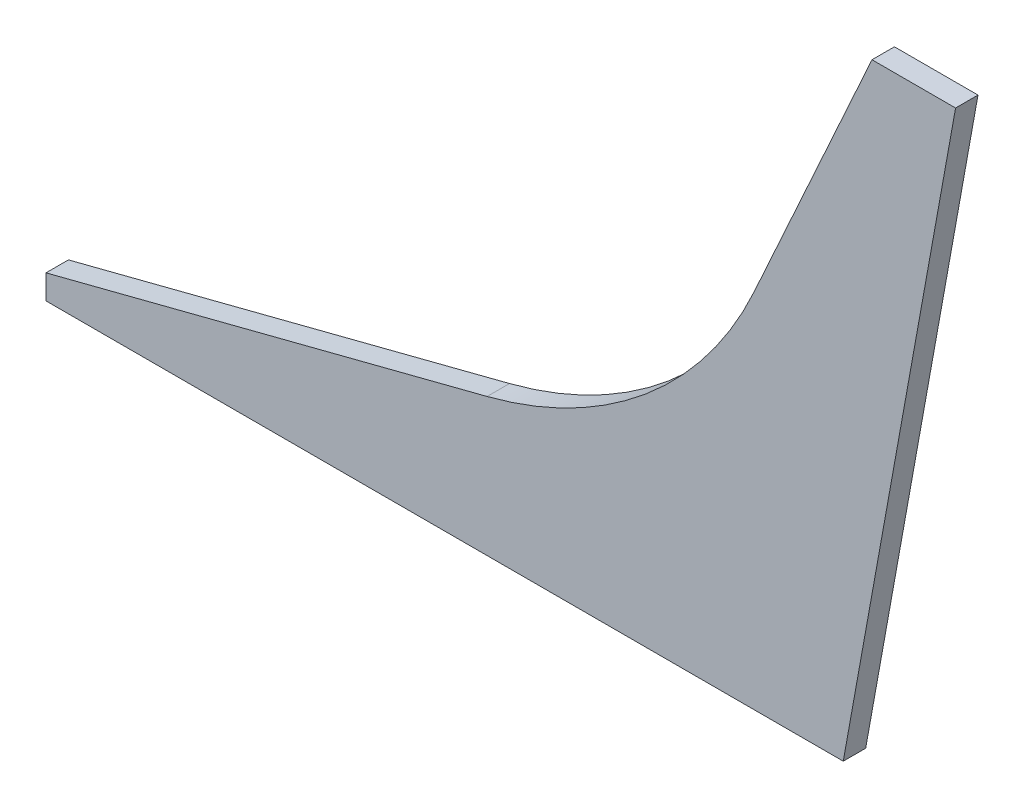
SolidWorks part; units mm, degrees
ref_plane "Front Plane" through (0, 0, 0) normal (0, 0, 1) x (1, 0, 0)
ref_plane "Top Plane" through (0, 0, 0) normal (0, 1, 0) x (1, 0, 0)
ref_plane "Right Plane" through (0, 0, 0) normal (1, 0, 0) x (0, 0, -1)
sketch "Sketch1" plane through (0, 0, 0) normal (0, 0, 1) x (1, 0, 0)
  line L0 (-236.7294, 0) -> (236.7294, 0) construction
  line L1 (-236.7294, 0) -> (0, 0)
  line L2 (0, 0) -> (357.8768, 0)
  line L3 (357.8768, 0) -> (396.7304, 416)
  line L4 (396.7304, 416) -> (315.8328, 416)
  line L5 (315.8328, 416) -> (236.9831, 242.1445)
  line L6 (58.3523, 92.1777) -> (-236.7294, 16.2749)
  line L7 (-236.7294, 16.2749) -> (-236.7294, 0)
  arc A0 (236.9831, 242.1445) -> (58.3523, 92.1777) centre (-8.9093, 353.6655) cw
  point P4 (0, 0)
  point P39 (183.5766, 124.3887)
  dimension "D4" = 270
  dimension "D3" = 416
extrude "Boss-Extrude1" add sketch "Sketch1" along normal blind 15
sketch "Sketch2" plane through (0, 0, 15) normal (0, 0, 1) x (1, 0, 0)
  line L0 (396.7304, 416) -> (357.8768, 0)
  line L1 (357.8768, 0) -> (296.5972, 0)
  line L2 (-236.7294, 0) -> (357.8768, 0) construction
  line L3 (296.5972, 0) -> (371.7349, 416)
  line L4 (396.7304, 416) -> (315.8328, 416) construction
  line L5 (371.7349, 416) -> (396.7304, 416)
  line L6 (329.6881, 183.2077) -> (374.9881, 183.2077) construction
  dimension "D1" = 45.3
extrude "Cut-Extrude1" cut sketch "Sketch2" against normal through all both and the other way through all
scale "Scale1" scale about centroid uniform scaling yes scale factor 0.6
